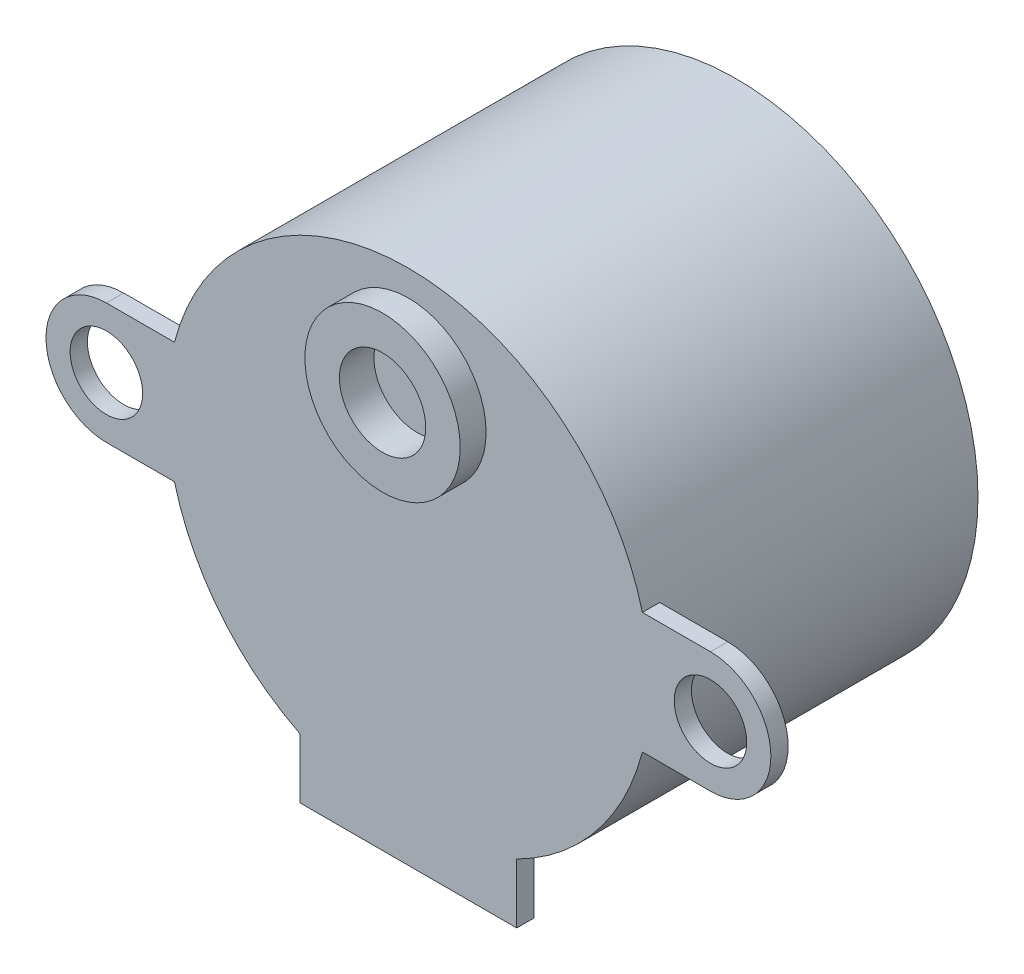
SolidWorks part; units mm, degrees
ref_plane "Plan de face" through (0, 0, 0) normal (0, 0, 1) x (1, 0, 0)
ref_plane "Plan de dessus" through (0, 0, 0) normal (0, 1, 0) x (1, 0, 0)
ref_plane "Plan de droite" through (0, 0, 0) normal (1, 0, 0) x (0, 0, -1)
sketch "Esquisse1" plane through (0, 0, 0) normal (0, 0, 1) x (1, 0, 0)
  line L0 (15.5277, 3.5) -> (15.5277, -3.5) construction
  line L1 (13.5554, 3.5) -> (17.5, 3.5)
  line L2 (17.5, -3.5) -> (13.5554, -3.5)
  line L3 (-13.5554, 3.5) -> (-17.5, 3.5)
  line L4 (-17.5, -3.5) -> (-13.5554, -3.5)
  line L5 (-17.5, 0) -> (17.5, 0) construction
  arc A0 (-13.5554, -3.5) -> (13.5554, -3.5) centre (0, 0) ccw
  arc A1 (17.5, 3.5) -> (17.5, -3.5) centre (17.5, 0) cw
  arc A2 (-17.5, 3.5) -> (-17.5, -3.5) centre (-17.5, 0) ccw
  circle A3 centre (-17.5, 0) radius 2.1
  circle A4 centre (17.5, 0) radius 2.1
  arc A5 (13.5554, 3.5) -> (-13.5554, 3.5) centre (0, 0) ccw
  point P3 (15.5277, 0)
  point P4 (15.5277, 3.5)
  point P18 (15.5277, -3.5)
  dimension "D1" = 28
  dimension "D2" = 7
  dimension "D3" = 35
  dimension "D4" = 4.2
extrude "Boss.-Extru.1" add sketch "Esquisse1" against normal blind 19
sketch "Esquisse2" plane through (0, 0, -19) normal (0, 0, -1) x (-1, 0, 0)
  line L0 (-13.5554, 3.5) -> (-17.5, 3.5)
  line L1 (-17.5, -3.5) -> (-13.5554, -3.5)
  line L2 (13.5554, 3.5) -> (17.5, 3.5)
  line L3 (17.5, -3.5) -> (13.5554, -3.5)
  arc A0 (-17.5, 3.5) -> (-17.5, -3.5) centre (-17.5, 0) ccw
  arc A1 (-17.5, 3.5) -> (-17.5, -3.5) centre (-17.5, 0) ccw construction
  arc A2 (17.5, 3.5) -> (17.5, -3.5) centre (17.5, 0) cw
  arc A3 (17.5, -3.5) -> (17.5, 3.5) centre (17.5, 0) ccw construction
  arc A4 (-13.5554, 3.5) -> (-13.5554, -3.5) centre (0, 0) ccw
  arc A5 (13.5554, -3.5) -> (13.5554, 3.5) centre (0, 0) ccw
extrude "Enlèv. mat.-Extru.1" cut sketch "Esquisse2" against normal blind 18
sketch "Esquisse3" plane through (0, 0, 0) normal (0, 0, 1) x (1, 0, 0)
  line L0 (0, 17.088) -> (0, -15.8248) construction
  line L1 (-19.1203, 8) -> (19.8305, 8) construction
  line L2 (-17.5, 0) -> (17.5, 0) construction
  circle A0 centre (0, 8) radius 4.5
  dimension "D1" = 8
extrude "Boss.-Extru.2" add sketch "Esquisse3" along normal blind 1.5
sketch "Esquisse4" plane through (0, 0, 1.5) normal (0, 0, 1) x (1, 0, 0)
  circle A0 centre (0, 8) radius 2.5
  dimension "D1" = 5
extrude "Enlèv. mat.-Extru.2" cut sketch "Esquisse4" against normal blind 2
sketch "Esquisse5" plane through (0, 0, 0) normal (0, 0, 1) x (1, 0, 0)
  line L0 (0, 0) -> (0, -18.6458) construction
  line L1 (-6.275, -15.975) -> (6.275, -15.975)
  line L2 (-6.275, -15.975) -> (-6.275, -12.515)
  line L3 (6.275, -15.975) -> (6.275, -12.515)
  arc A0 (-6.275, -12.515) -> (6.275, -12.515) centre (0, 0) ccw
  point P7 (0, -15.975)
  dimension "D1" = 12.55
  dimension "D3" = 28
  dimension "D2" = 15.975
extrude "Boss.-Extru.3" add sketch "Esquisse5" against normal blind 1
